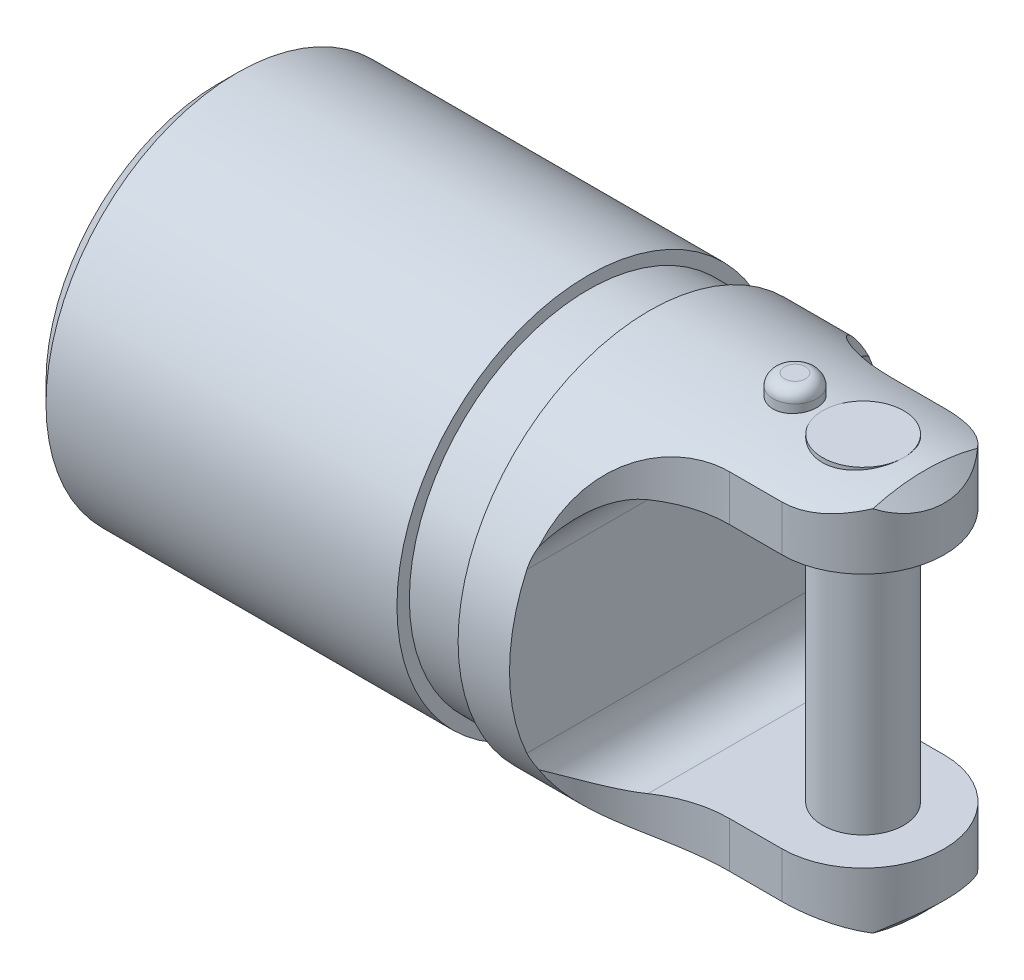
SolidWorks part; units mm, degrees
ref_plane "Front Plane" through (0, 0, 0) normal (0, 0, 1) x (1, 0, 0)
ref_plane "Top Plane" through (0, 0, 0) normal (0, 1, 0) x (1, 0, 0)
ref_plane "Right Plane" through (0, 0, 0) normal (1, 0, 0) x (0, 0, -1)
sketch "Sketch0" plane through (0, 0, 0) normal (0, 1, 0) x (1, 0, 0)
  line L0 (-42.8625, 0) -> (42.8625, 0) construction
  line L1 (-42.8625, 12.7) -> (-42.8625, -12.7) construction
  line L2 (-12.7, 6.35) -> (-12.7, -6.35) construction
  line L3 (-12.7, 6.35) -> (-6.35, 0) construction
  line L4 (-6.35, 0) -> (-12.7, -6.35) construction
  line L5 (-9.525, 3.175) -> (-9.525, -3.175) construction
  point P7 (-12.7, 0)
  point P8 (0, 0)
  point P12 (-9.525, 0)
sketch "Sketch1" plane through (0, 0, 0) normal (0, 1, 0) x (1, 0, 0)
  line L0 (-42.8625, 12.7) -> (5.3975, 12.7)
  line L1 (5.3975, 12.7) -> (5.3975, 0)
  line L2 (5.3975, 0) -> (-42.8625, 0)
  line L3 (-42.8625, 0) -> (-42.8625, 12.7)
  line L4 (-42.8625, 12.7) -> (-42.8625, -12.7) construction
  line L5 (-42.8625, 0) -> (42.8625, 0) construction
  line L11 (0, 0) -> (10.795, 0) construction
  circle A0 centre (0, 0) radius 10.795 construction
  dimension "D1" = 21.59
  dimension "D3" = 48.26
revolve "Revolve1" add sketch "Sketch1" angle 360 about L0
chamfer "Chamfer1" distance 1.27 angle 45 2 edges at (-42.8625, 0, 12.7) (5.3975, 0, 12.7)
sketch "Sketch2" plane through (0, 0, 0) normal (0, 1, 0) x (1, 0, 0)
  line L0 (-12.7, 0) -> (-9.525, 0) construction
  line L4 (-42.8625, 0) -> (5.3975, 0) construction
  line L5 (-10.795, 12.7) -> (10.795, 12.7)
  line L6 (10.795, 12.7) -> (10.795, -12.7)
  line L7 (10.795, -12.7) -> (-10.795, -12.7)
  line L8 (0, 5.3975) -> (0, 0) construction
  line L9 (0, 5.3975) -> (-3.4925, 5.3975)
  line L10 (-10.795, 12.7) -> (-10.795, -12.7) construction
  line L11 (0, -5.3975) -> (-3.4925, -5.3975)
  line L12 (-42.8625, 12.7) -> (5.3975, 12.7) construction
  arc A0 (-10.795, 12.7) -> (-3.4925, 5.3975) centre (-3.4925, 12.7) ccw
  arc A1 (0, -5.3975) -> (0, 5.3975) centre (0, 0) ccw
  arc A2 (-3.4925, -5.3975) -> (-10.795, -12.7) centre (-3.4925, -12.7) ccw
  circle A3 centre (0, 0) radius 10.795 construction
  dimension "D1" = 10.795
extrude "Extrude1" cut sketch "Sketch2" against normal through all and the other way through all
sketch "Sketch4" plane through (-42.8625, 0, 0) normal (-1, 0, 0) x (0, 0, 1)
  circle A0 centre (0, 0) radius 6.35
extrude "Extrude4" cut sketch "Sketch4" against normal up to vertex
sketch "Sketch3" plane through (0, 0, 0) normal (0, 0, 1) x (1, 0, 0)
  line L1 (-7.62, 8.4582) -> (10.795, 8.4582)
  line L2 (-10.795, 5.2832) -> (-10.795, -5.2832)
  line L3 (-7.62, -8.4582) -> (10.795, -8.4582)
  line L4 (10.795, 8.4582) -> (10.795, -8.4582)
  line L6 (-10.795, 0) -> (-3.4925, 0) construction
  line L7 (-3.4925, -11.496) -> (-3.4925, 11.496) construction
  line L8 (10.795, 0) -> (-10.795, 0) construction
  arc A0 (-10.795, -5.2832) -> (-7.62, -8.4582) centre (-7.62, -5.2832) ccw
  arc A1 (-10.795, 5.2832) -> (-7.62, 8.4582) centre (-7.62, 5.2832) cw
  dimension "D2" = 3.175
  dimension "D1" = 16.9164
extrude "Extrude3" cut sketch "Sketch3" against normal through all and the other way through all
sketch "Sketch6" plane through (0, 0, 0) normal (0, 1, 0) x (1, 0, 0)
  line L0 (-42.8625, 0) -> (42.8625, 0) construction
  line L1 (5.3975, 0) -> (2.6987, 0) construction
  line L2 (2.6987, 0) -> (0, 0) construction
  circle A0 centre (0, 0) radius 2.6987
  arc A1 (0, -5.3975) -> (0, 5.3975) centre (0, 0) ccw construction
  dimension "D1" = 5.3975
extrude "Extrude6" cut sketch "Sketch6" against normal through all and the other way through all
sketch "Sketch21" plane through (0, 0, 0) normal (0, -1, 0) x (1, 0, 0)
  line L0 (-42.8625, 0) -> (42.8625, 0) construction
  line L1 (-6.35, 0) -> (-2.6988, 0) construction
  circle A0 centre (-4.5244, 0) radius 1.4605
  circle A1 centre (0, 0) radius 2.6987 construction
  dimension "D2" = 2.921
  dimension "D1" = 3.6512
extrude "Boss-Extrude1" add sketch "Sketch21" against normal mid plane 27.94
fillet "Fillet1" radius 0.762 2 edges at (-4.5244, 13.97, -1.4605) (-4.5244, -13.97, -1.4605)
sketch "Sketch22" plane through (0, 0, 0) normal (0, 0, 1) x (1, 0, 0)
  line L4 (10.795, 8.4582) -> (-7.62, 8.4582)
  line L5 (10.795, -8.4582) -> (10.795, 8.4582)
  line L6 (-7.62, -8.4582) -> (10.795, -8.4582)
  line L7 (-10.795, 5.2832) -> (-10.795, -5.2832)
  line L8 (10.795, 8.4582) -> (-7.62, 8.4582)
  line L9 (10.795, -8.4582) -> (10.795, 8.4582)
  line L10 (-7.62, -8.4582) -> (10.795, -8.4582)
  line L11 (-10.795, 5.2832) -> (-10.795, -5.2832)
  arc A2 (-10.795, -5.2832) -> (-7.62, -8.4582) centre (-7.62, -5.2832) ccw
  arc A3 (-7.62, 8.4582) -> (-10.795, 5.2832) centre (-7.62, 5.2832) ccw
  arc A4 (-10.795, -5.2832) -> (-7.62, -8.4582) centre (-7.62, -5.2832) ccw
  arc A5 (-7.62, 8.4582) -> (-10.795, 5.2832) centre (-7.62, 5.2832) ccw
  dimension "D1" = 0
extrude "Cut-Extrude3" cut sketch "Sketch22" against normal through all and the other way through all
sketch "Sketch23" plane through (0, 0, 0) normal (0, 1, 0) x (1, 0, 0)
  line L0 (-42.8625, 0) -> (42.8625, 0) construction
  line L1 (-42.8625, 0) -> (42.8625, 0) construction
  line L3 (-18.2753, -12.7) -> (-14.2113, -12.7)
  line L4 (-18.2753, -12.7) -> (-18.2753, -11.8745)
  line L5 (-18.2753, -11.8745) -> (-14.2113, -11.8745)
  line L6 (-14.2113, -12.7) -> (-14.2113, -11.8745)
  dimension "D1" = 24.5872
  dimension "D2" = 4.064
  dimension "D3" = 23.749
revolve "Cut-Revolve1" cut sketch "Sketch23" angle 360 about L1
mirror "Mirror1" [suppressed] about plane through (0, 0, 0) normal (1, 0, 0)
move or copy body "Body-Move/Copy1" [suppressed] bodies to move or copy 110 copy no rotation origin (0, 0, 0) rotation axis (1, 0, 0) rotation angle 90
sketch "Sketch18" [suppressed] plane through (0, 0, 0) normal (0, 1, 0) x (1, 0, 0)
  line L0 (-42.8625, -6.35) -> (-12.7, -6.35)
  line L3 (-42.8625, 6.35) -> (-12.7, 6.35)
  line L4 (-12.7, 6.35) -> (-12.7, -6.35)
  line L5 (12.7, 6.35) -> (12.7, -6.35)
  line L6 (12.7, -6.35) -> (42.8625, -6.35)
  line L7 (12.7, 6.35) -> (42.8625, 6.35)
  line L8 (0, 0) -> (12.7, 0) construction
  line L9 (42.8625, -11.43) -> (42.8625, 11.43) construction
  line L10 (-12.7, 6.35) -> (-12.7, -6.35) construction
  line L12 (-42.8625, 0) -> (42.8625, 0) construction
sketch "Sketch10" [suppressed] plane through (0, 0, 0) normal (0, 0, 1) x (1, 0, 0)
  line L0 (-4.0481, 8.4582) -> (4.0481, -8.4582) construction
  line L1 (-4.0481, 8.4582) -> (4.0481, 8.4582)
  line L2 (-4.0481, 8.4582) -> (-4.0481, -8.4582)
  line L3 (-4.0481, -8.4582) -> (4.0481, -8.4582)
  line L4 (4.0481, 8.4582) -> (4.0481, -8.4582)
  line L5 (0, 8.4582) -> (5.3975, 8.4582) construction
  line L6 (-2.6988, 0) -> (-5.3975, 0) construction
  arc A0 (-4.1275, -3.478) -> (0, -5.3975) centre (0, 0) ccw construction
  circle A1 centre (0, 0) radius 2.6988 construction
  point P9 (-4.0481, 0)
extrude "Extrude10" [suppressed] add sketch "Sketch10" against normal up to surface and the other way up to surface separate body
sketch "Sketch20" [suppressed] plane through (0, 8.4582, 0) normal (0, 1, 0) x (1, 0, 0)
  line L4 (4.0481, 8.4582) -> (-4.0481, 8.4582) construction
  line L5 (4.0481, -8.4582) -> (-4.0481, -8.4582) construction
  line L6 (-4.0481, 8.4582) -> (-4.0481, -8.4582) construction
  line L7 (4.0481, 8.4582) -> (4.0481, -8.4582) construction
  line L8 (5.0641, -9.4742) -> (5.0641, 9.4742)
  line L9 (5.0641, 9.4742) -> (-5.0641, 9.4742)
  line L10 (-5.0641, 9.4742) -> (-5.0641, -9.4742)
  line L11 (-5.0641, -9.4742) -> (5.0641, -9.4742)
  line L12 (5.0641, -9.4742) -> (5.0641, 9.4742)
  line L13 (5.0641, 9.4742) -> (3.3734, 9.4742)
  line L14 (-5.0641, 9.4742) -> (-5.0641, -9.4742)
  line L15 (-5.0641, -9.4742) -> (-3.3734, -9.4742)
  line L16 (-3.3734, 8.4582) -> (-3.3734, 9.4742)
  line L17 (3.3734, 8.4582) -> (3.3734, 9.4742)
  line L18 (3.3734, -8.4582) -> (3.3734, -9.4742)
  line L19 (-3.3734, -8.4582) -> (-3.3734, -9.4742)
  line L20 (-3.3734, 9.4742) -> (-5.0641, 9.4742)
  line L21 (3.3734, -9.4742) -> (5.0641, -9.4742)
  line L22 (-42.8625, 0) -> (5.3975, 0) construction
  line L23 (4.0481, 8.4582) -> (-4.0481, 8.4582) construction
  arc A0 (3.3734, 8.4582) -> (3.3734, -8.4582) centre (-49.3072, 0) cw
  arc A1 (-3.3734, 8.4582) -> (-3.3734, -8.4582) centre (49.3072, 0) ccw
  dimension "D2" = 8.0963
  dimension "D3" = 0.6747
  dimension "D1" = 1.016
extrude "Cut-Extrude2" [suppressed] cut sketch "Sketch20" against normal through all
sketch "Sketch13" plane through (0, 0, 0) normal (0, 1, 0) x (1, 0, 0)
  circle A0 centre (0, 0) radius 2.6987 construction
  circle A1 centre (0, 0) radius 2.6987
extrude "Extrude13" [suppressed] cut sketch "Sketch13" against normal through all and the other way through all
sketch "Sketch14" plane through (0, 0, 0) normal (0, 1, 0) x (1, 0, 0)
  circle A1 centre (0, 0) radius 2.6987
  circle A2 centre (0, 0) radius 2.6987
  dimension "D1" = 0
extrude "Extrude14" add sketch "Sketch14" along normal mid plane 25.4 separate body
sketch "Sketch15" [suppressed] plane through (0, 0, 0) normal (0, 0, 1) x (1, 0, 0)
  circle A0 centre (0, 0) radius 2.6987 construction
  circle A1 centre (0, 0) radius 2.6988
extrude "Extrude15" [suppressed] cut sketch "Sketch15" against normal through all and the other way through all
sketch "Sketch16" [suppressed] plane through (0, 0, 0) normal (0, 0, 1) x (1, 0, 0)
  circle A1 centre (0, 0) radius 2.6988
  circle A2 centre (0, 0) radius 2.6988
  dimension "D1" = 0
extrude "Extrude16" [suppressed] add sketch "Sketch16" along normal mid plane 25.4
chamfer "Chamfer3" [suppressed] distance 0.635 angle 45
move or copy body "Body-Move/Copy2" [suppressed] bodies to move or copy 111 copy no rotation origin (0, 0, 0) rotation axis (0, 0, -1) rotation angle 35
equation "\"D2@Sketch3\" = \"D1@Sketch3\" / 4"
equation "\"D1@Extrude14\" = \"OD@Sketch0\""
equation "\"D1@Extrude16\" = \"D1@Extrude14\""
equation "\"D1@Sketch3\" = \"OD@Sketch0\"*.666"
equation "\"D1@Chamfer1\" = \"OD@Sketch0\"/20"
equation "\"D1@Chamfer3\" = \"D1@Chamfer1\"*.50"
equation "\"D3@Sketch20\" = \"D2@Sketch20\"/12"
equation "\"D1@Sketch1\" = \"OD@Sketch0\"*.85"
equation "\"D2@Sketch21\" = \"D1@Sketch21\"*.8"
equation "\"D1@Boss-Extrude1\" = \"OD@Sketch0\"*1.1"
